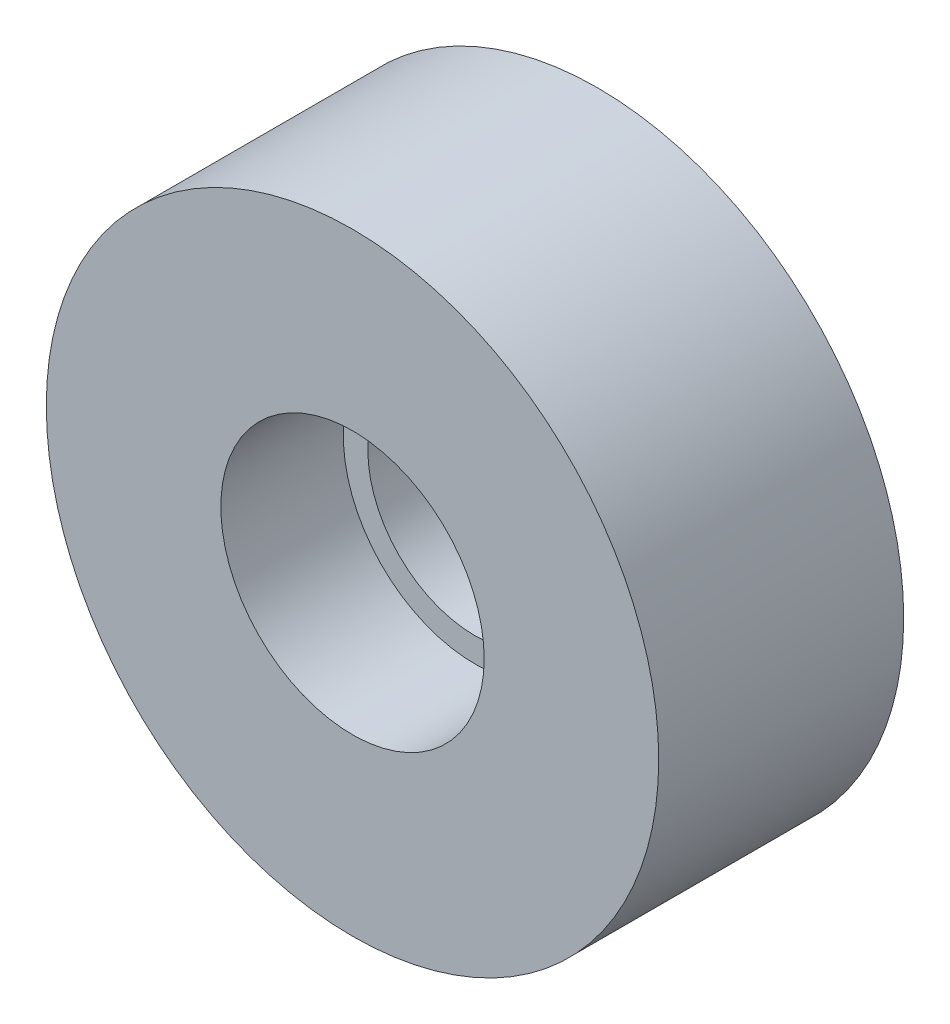
SolidWorks part; units mm, degrees
ref_plane "Plan de face" through (0, 0, 0) normal (0, 0, 1) x (1, 0, 0)
ref_plane "Plan de dessus" through (0, 0, 0) normal (0, 1, 0) x (1, 0, 0)
ref_plane "Plan de droite" through (0, 0, 0) normal (1, 0, 0) x (0, 0, -1)
sketch "Esquisse1" plane through (0, 0, 0) normal (0, 0, 1) x (1, 0, 0)
  circle A0 centre (0, 0) radius 5
  dimension "D1" = 10
extrude "Boss.-Extru.1" add sketch "Esquisse1" along normal blind 4
sketch "Esquisse2" plane through (0, 0, 4) normal (0, 0, 1) x (1, 0, 0)
  circle A0 centre (0, 0) radius 2.15
  dimension "D1" = 4.3
extrude "Enlèv. mat.-Extru.1" cut sketch "Esquisse2" against normal blind 2
sketch "Esquisse3" plane through (0, 0, 0) normal (0, 0, -1) x (-1, 0, 0)
  circle A0 centre (0, 0) radius 1.75
  dimension "D1" = 3.5
extrude "Enlèv. mat.-Extru.2" cut sketch "Esquisse3" against normal through all
